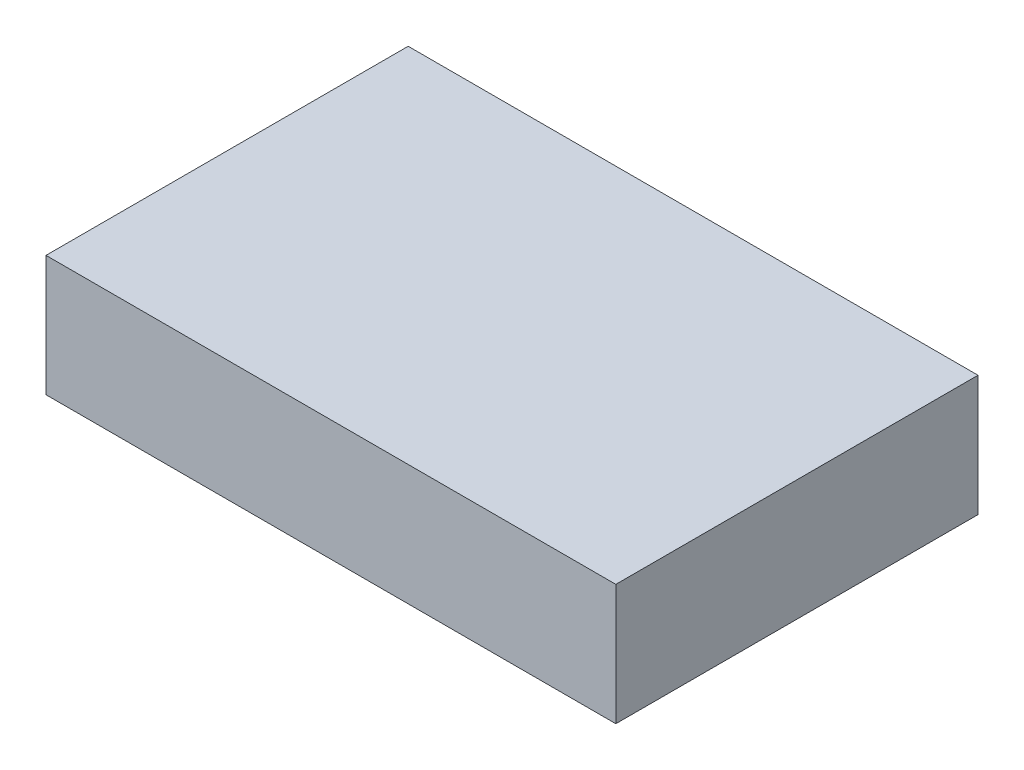
SolidWorks part; units mm, degrees
ref_plane "Front Plane" through (0, 0, 0) normal (0, 0, 1) x (1, 0, 0)
ref_plane "Top Plane" through (0, 0, 0) normal (0, 1, 0) x (1, 0, 0)
ref_plane "Right Plane" through (0, 0, 0) normal (1, 0, 0) x (0, 0, -1)
sketch "Sketch1" plane through (0, 0, 0) normal (0, 1, 0) x (1, 0, 0)
  line L1 (32.3161, 16.2331) -> (62.2881, 16.2331)
  line L2 (32.3161, 16.2331) -> (32.3161, -2.8169)
  line L3 (32.3161, -2.8169) -> (62.2881, -2.8169)
  line L4 (62.2881, 16.2331) -> (62.2881, -2.8169)
  dimension "D1" = 29.972
  dimension "D2" = 19.05
extrude "Boss-Extrude1" add sketch "Sketch1" along normal blind 6.35
